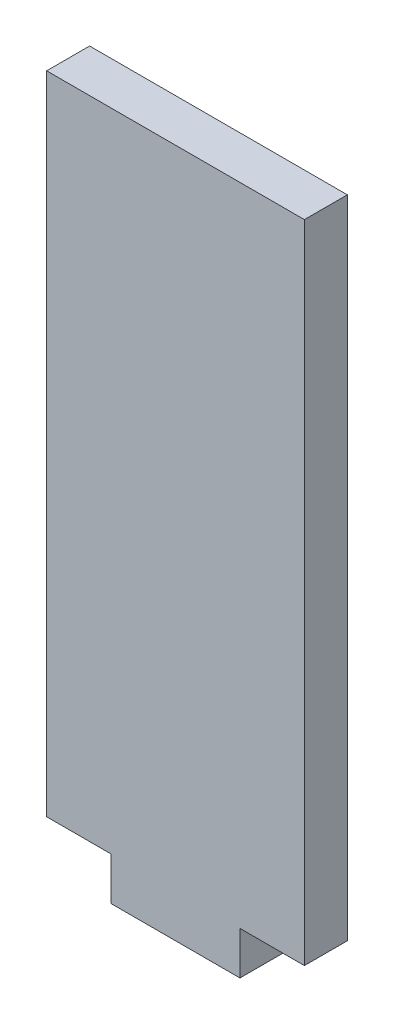
SolidWorks part; units mm, degrees
ref_plane "前视基准面" through (0, 0, 0) normal (0, 0, 1) x (1, 0, 0)
ref_plane "上视基准面" through (0, 0, 0) normal (0, 1, 0) x (1, 0, 0)
ref_plane "右视基准面" through (0, 0, 0) normal (1, 0, 0) x (0, 0, -1)
sketch "草图1" plane through (0, 0, 0) normal (0, 0, 1) x (1, 0, 0)
  line L0 (-6, 0) -> (-6, 15)
  line L1 (-6, 0) -> (-3, 0)
  line L3 (6, 0) -> (6, 15)
  line L4 (-3, 0) -> (-3, -2)
  line L6 (-3, -2) -> (3, -2)
  line L7 (3, 0) -> (3, -2)
  line L8 (-6, 15) -> (-6, 30.0788)
  line L9 (-6, 30.0788) -> (6, 30.0788)
  line L10 (6, 30.0788) -> (6, 15)
  line L11 (3, 0) -> (6, 0)
extrude "凸台-拉伸1" add sketch "草图1" along normal blind 2 contours L9 L10 L3 L11 L7 L6 L4 L1 L0 L8
sketch3d "3D草图1"
  spline S0 degree 3 poles (-3.7277, 8.6658, 2) (-3.7071, 8.14, 2) (-3.6715, 7.8825, 2) (-3.5517, 7.3777, 2) (-3.4663, 7.1278, 2) (-3.2498, 6.6526, 2) (-3.1198, 6.4281, 2) (-2.8169, 6.0053, 2) (-2.6421, 5.8058, 2) (-2.2627, 5.4505, 2) (-2.0571, 5.2923, 2) (-1.613, 5.0161, 2) (-1.3766, 4.8998, 2) (-0.8909, 4.7179, 2) (-0.6382, 4.6505, 2) (-0.12, 4.5669, 2) (0.1393, 4.5514, 2) (0.6582, 4.5714, 2) (0.9206, 4.6079, 2) (1.427, 4.7307, 2) (1.6718, 4.8165, 2) (2.1447, 5.0367, 2) (2.3723, 5.1718, 2) (2.7905, 5.4793, 2) (2.9839, 5.653, 2) (3.3385, 6.0413, 2) (3.4942, 6.2501, 2) (3.763, 6.6941, 2) (3.8771, 6.9322, 2) (4.0557, 7.4229, 2) (4.1203, 7.6742, 2) (4.2009, 8.1883, 2) (4.2163, 8.453, 2) (4.1961, 8.9723, 2) (4.1612, 9.2295, 2) (4.0408, 9.7385, 2) (3.9555, 9.9876, 2) (3.7409, 10.4598, 2) (3.6105, 10.6861, 2) (3.3048, 11.113, 2) (3.1335, 11.3083, 2) (2.7551, 11.6635, 2) (2.5454, 11.8249, 2) (2.1026, 12.1004, 2) (1.87, 12.2151, 2) (1.3824, 12.3983, 2) (1.1263, 12.4664, 2) (0.6136, 12.5494, 2) (0.3545, 12.5656, 2) (-0.1697, 12.5457, 2) (-0.4291, 12.5095, 2) (-0.9335, 12.3877, 2) (-1.1822, 12.3009, 2) (-1.6564, 12.0801, 2) (-1.8796, 11.9477, 2) (-2.299, 11.64, 2) (-2.4962, 11.4627, 2) (-2.847, 11.0788, 2) (-3.0027, 10.8711, 2) (-3.2739, 10.4238, 2) (-3.3876, 10.1863, 2) (-3.5654, 9.6989, 2) (-3.631, 9.446, 2) (-3.7125, 8.9269, 2) (-3.7277, 8.6658, 2) (-3.7071, 8.14, 2) (-3.6715, 7.8825, 2) knots -0.03125 -0.03125 0 0 0.03125 0.03125 0.0625 0.0625 0.09375 0.09375 0.125 0.125 0.15625 0.15625 0.1875 0.1875 0.21875 0.21875 0.25 0.25 0.28125 0.28125 0.3125 0.3125 0.34375 0.34375 0.375 0.375 0.40625 0.40625 0.4375 0.4375 0.46875 0.46875 0.5 0.5 0.53125 0.53125 0.5625 0.5625 0.59375 0.59375 0.625 0.625 0.65625 0.65625 0.6875 0.6875 0.71875 0.71875 0.75 0.75 0.78125 0.78125 0.8125 0.8125 0.84375 0.84375 0.875 0.875 0.90625 0.90625 0.9375 0.9375 0.96875 0.96875 1 1 1.03125 1.03125 1.0625 only from (-3.7174, 8.4029, 2) to (-3.7174, 8.4029, 2)
  spline S1 degree 3 poles (-3.7277, 8.6658, 2) (-3.7071, 8.14, 2) (-3.6715, 7.8825, 2) (-3.5517, 7.3777, 2) (-3.4663, 7.1278, 2) (-3.2498, 6.6526, 2) (-3.1198, 6.4281, 2) (-2.8169, 6.0053, 2) (-2.6421, 5.8058, 2) (-2.2627, 5.4505, 2) (-2.0571, 5.2923, 2) (-1.613, 5.0161, 2) (-1.3766, 4.8998, 2) (-0.8909, 4.7179, 2) (-0.6382, 4.6505, 2) (-0.12, 4.5669, 2) (0.1393, 4.5514, 2) (0.6582, 4.5714, 2) (0.9206, 4.6079, 2) (1.427, 4.7307, 2) (1.6718, 4.8165, 2) (2.1447, 5.0367, 2) (2.3723, 5.1718, 2) (2.7905, 5.4793, 2) (2.9839, 5.653, 2) (3.3385, 6.0413, 2) (3.4942, 6.2501, 2) (3.763, 6.6941, 2) (3.8771, 6.9322, 2) (4.0557, 7.4229, 2) (4.1203, 7.6742, 2) (4.2009, 8.1883, 2) (4.2163, 8.453, 2) (4.1961, 8.9723, 2) (4.1612, 9.2295, 2) (4.0408, 9.7385, 2) (3.9555, 9.9876, 2) (3.7409, 10.4598, 2) (3.6105, 10.6861, 2) (3.3048, 11.113, 2) (3.1335, 11.3083, 2) (2.7551, 11.6635, 2) (2.5454, 11.8249, 2) (2.1026, 12.1004, 2) (1.87, 12.2151, 2) (1.3824, 12.3983, 2) (1.1263, 12.4664, 2) (0.6136, 12.5494, 2) (0.3545, 12.5656, 2) (-0.1697, 12.5457, 2) (-0.4291, 12.5095, 2) (-0.9335, 12.3877, 2) (-1.1822, 12.3009, 2) (-1.6564, 12.0801, 2) (-1.8796, 11.9477, 2) (-2.299, 11.64, 2) (-2.4962, 11.4627, 2) (-2.847, 11.0788, 2) (-3.0027, 10.8711, 2) (-3.2739, 10.4238, 2) (-3.3876, 10.1863, 2) (-3.5654, 9.6989, 2) (-3.631, 9.446, 2) (-3.7125, 8.9269, 2) (-3.7277, 8.6658, 2) (-3.7071, 8.14, 2) (-3.6715, 7.8825, 2) knots -0.03125 -0.03125 0 0 0.03125 0.03125 0.0625 0.0625 0.09375 0.09375 0.125 0.125 0.15625 0.15625 0.1875 0.1875 0.21875 0.21875 0.25 0.25 0.28125 0.28125 0.3125 0.3125 0.34375 0.34375 0.375 0.375 0.40625 0.40625 0.4375 0.4375 0.46875 0.46875 0.5 0.5 0.53125 0.53125 0.5625 0.5625 0.59375 0.59375 0.625 0.625 0.65625 0.65625 0.6875 0.6875 0.71875 0.71875 0.75 0.75 0.78125 0.78125 0.8125 0.8125 0.84375 0.84375 0.875 0.875 0.90625 0.90625 0.9375 0.9375 0.96875 0.96875 1 1 1.03125 1.03125 1.0625 only from (-3.7174, 8.4029, 2) to (-3.7174, 8.4029, 2)
